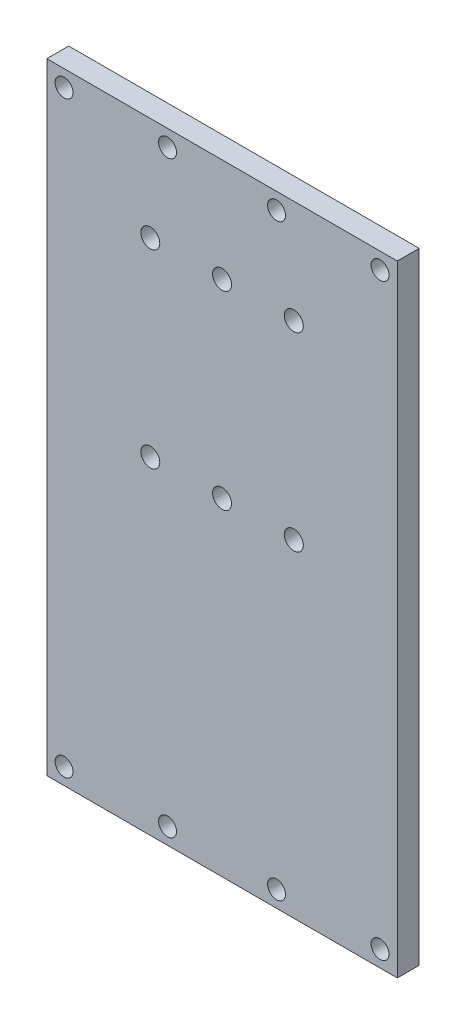
SolidWorks part; units mm, degrees
ref_plane "Plano frontal" through (0, 0, 0) normal (0, 0, 1) x (1, 0, 0)
ref_plane "Plano superior" through (0, 0, 0) normal (0, 1, 0) x (1, 0, 0)
ref_plane "Plano direito" through (0, 0, 0) normal (1, 0, 0) x (0, 0, -1)
sketch "Esboço1" plane through (0, 0, 0) normal (0, 0, 1) x (1, 0, 0)
  line L0 (50.8, 90) -> (-50.8, -90) construction
  line L1 (-50.8, 90) -> (50.8, 90)
  line L2 (-50.8, 90) -> (-50.8, -90)
  line L3 (-50.8, -90) -> (50.8, -90)
  line L4 (50.8, 90) -> (50.8, -90)
  dimension "D1" = 101.6
  dimension "D2" = 180
extrude "Ressalto-extrusão1" add sketch "Esboço1" along normal blind 6.35
sketch "Esboço2" plane through (0, 0, 6.35) normal (0, 0, 1) x (1, 0, 0)
  line L0 (0, 90) -> (0, -90) construction
  line L1 (50.8, 90) -> (-50.8, 90) construction
  line L2 (-50.8, -90) -> (50.8, -90) construction
  line L3 (-50.8, 85.24) -> (0, 85.24) construction
  line L4 (-50.8, 90) -> (-50.8, -90) construction
  line L5 (0, 0) -> (50.8, 0) construction
  line L6 (50.8, -90) -> (50.8, 90) construction
  line L7 (-20.8, 60) -> (20.8, 60) construction
  line L8 (20.8, 60) -> (20.8, 5) construction
  line L9 (20.8, 5) -> (-20.8, 5) construction
  line L10 (-20.8, 5) -> (-20.8, 60) construction
  line L11 (-20.8, 32.5) -> (0, 32.5) construction
  circle A0 centre (-45.8, 85.24) radius 2.6
  circle A1 centre (-15.8, 85.24) radius 2.6
  circle A2 centre (15.8, 85.24) radius 2.6
  circle A3 centre (45.8, 85.24) radius 2.6
  circle A4 centre (45.8, -85.24) radius 2.6
  circle A5 centre (15.8, -85.24) radius 2.6
  circle A6 centre (-15.8, -85.24) radius 2.6
  circle A7 centre (-45.8, -85.24) radius 2.6
  circle A8 centre (20.8, 60) radius 2.75
  circle A9 centre (0, 60) radius 2.75
  circle A10 centre (-20.8, 60) radius 2.75
  circle A11 centre (20.8, 5) radius 2.75
  circle A12 centre (0, 5) radius 2.75
  circle A13 centre (-20.8, 5) radius 2.75
  dimension "D2" = 5.2
  dimension "D3" = 5.2
  dimension "D10" = 5.5
  dimension "D11" = 5.5
  dimension "D1" = 4.76
  dimension "D4" = 5
  dimension "D5" = 35
  dimension "D6" = 30
  dimension "D8" = 30
  dimension "D9" = 85
extrude "Corte-extrusão1" cut sketch "Esboço2" against normal up to next
